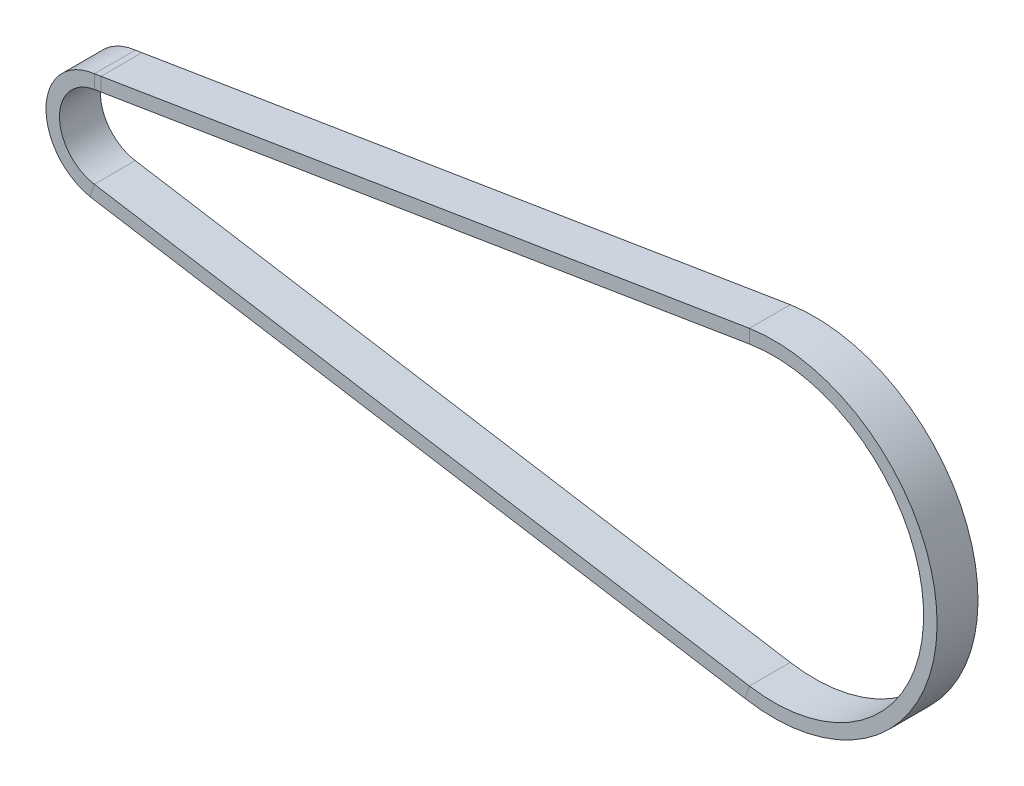
SolidWorks part; units mm, degrees
ref_plane "Front Plane" through (0, 0, 0) normal (0, 0, 1) x (1, 0, 0)
ref_plane "Top Plane" through (0, 0, 0) normal (0, 1, 0) x (1, 0, 0)
ref_plane "Right Plane" through (0, 0, 0) normal (1, 0, 0) x (0, 0, -1)
sketch "Sketch2" plane through (0, 0, 0) normal (0, 0, 1) x (1, 0, 0)
  line L0 (0, 0) -> (1, 0) construction
  line L1 (0, 0) -> (0, 1) construction
  line L2 (-3.1224, 19.1067) -> (301.7895, 68.9356)
  line L3 (301.7895, -68.9356) -> (-3.1224, -19.1067)
  arc A0 (-3.1224, -19.1067) -> (-3.1224, 19.1067) centre (0, 0) cw
  arc A1 (301.7895, 68.9356) -> (301.7895, -68.9356) centre (313.055, 0) cw
sketch "Sketch3" plane through (0, 0, 0) normal (1, 0, 0) x (0, 0, -1)
  line L0 (-9.525, 19.6169) -> (9.525, 19.6169)
  line L2 (9.525, 19.6169) -> (9.525, 25.9669)
  line L3 (9.525, 25.9669) -> (-9.525, 25.9669)
  line L4 (-9.525, 25.9669) -> (-9.525, 19.6169)
  point P3 (0, 19.6169)
  point P5 (0, 0)
  dimension "D1" = 19.05
  dimension "D2" = 6.35
sweep "Sweep1" add profiles "Sketch3" path "Sketch2"
